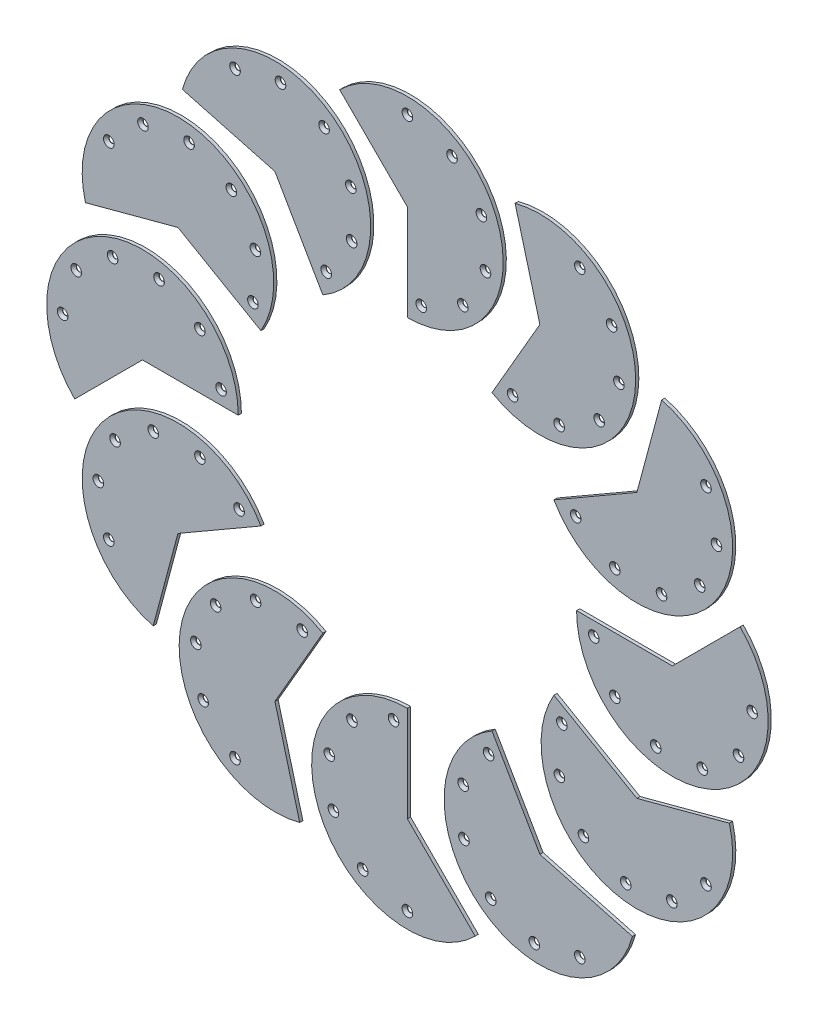
SolidWorks part; units mm, degrees
ref_plane "Front Plane" through (0, 0, 0) normal (0, 0, 1) x (1, 0, 0)
ref_plane "Top Plane" through (0, 0, 0) normal (0, 1, 0) x (1, 0, 0)
ref_plane "Right Plane" through (0, 0, 0) normal (1, 0, 0) x (0, 0, -1)
sketch "Sketch1" plane through (0, 0, 0) normal (0, 0, 1) x (1, 0, 0)
  line L0 (0, 0) -> (53.8815, -53.8815)
  line L1 (0, 0) -> (0, 76.2)
  arc A0 (0, 76.2) -> (53.8815, -53.8815) centre (0, 0) ccw
  dimension "D1" = 45
  dimension "D2" = 76.2
extrude "Boss-Extrude1" add sketch "Sketch1" along normal blind 2.54
hole_wizard "CSK for #8 Flat Head Machine Screw1" positions "Sketch2" profile "Sketch3" countersink size "#8" standard "ANSI Inch" end condition up to next
sketch "Sketch2" plane through (0, 0, 2.54) normal (0, 0, 1) x (1, 0, 0)
  line L0 (0, 0) -> (0, -63.5) construction
  point P0 (0, -63.5)
  dimension "D1" = 63.5
sketch "Sketch3" plane through (0, -63.5, 2.54) normal (1, 0, 0) x (0, -1, 0)
  line L0 (0, 0) -> (0, 2.54)
  line L1 (0, 2.54) -> (2.2479, 2.54)
  line L2 (2.2479, 2.54) -> (2.2479, 2.2645)
  line L3 (2.2479, 2.2645) -> (4.2164, 0)
  line L5 (4.2164, 0) -> (0, 0)
  line L6 (-2.2479, 2.2645) -> (-4.2164, 0) construction
  line L11 (0, -6.35) -> (0, 107.95) construction
  dimension "Thru Hole Dia." = 4.4958
  dimension "Thru Hole Depth" = 2.54
  dimension "Near C'Sink Dia." = 8.4328
  dimension "Near C'Sink Angle" = 82
pattern_circular "CirPattern1" count 6 over 170 about axis through (0, 0, 0) along (0, 0, 1) of "CSK for #8 Flat Head Machine Screw1"
sketch "Sketch4" plane through (0, 0, 0) normal (1, 0, 0) x (0, 0, -1)
  line L0 (-69.6312, 210.7945) -> (116.8954, 210.7945)
pattern_circular "CirPattern2" count 12 over 360 about axis through (0, 210.7945, 0) along (0, 0, 1) of bodies 103
